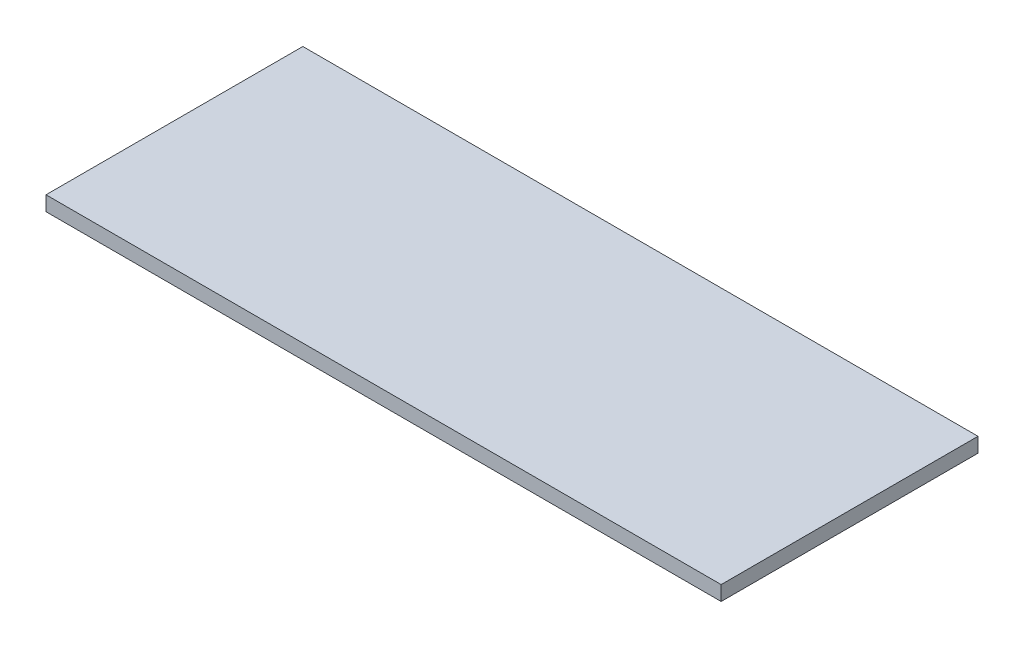
SolidWorks part; units mm, degrees
ref_plane "Front Plane" through (0, 0, 0) normal (0, 0, 1) x (1, 0, 0)
ref_plane "Top Plane" through (0, 0, 0) normal (0, 1, 0) x (1, 0, 0)
ref_plane "Right Plane" through (0, 0, 0) normal (1, 0, 0) x (0, 0, -1)
sketch "Sketch1" plane through (0, 0, 0) normal (0, 1, 0) x (1, 0, 0)
  line L1 (0, 0) -> (460, 0)
  line L2 (0, 0) -> (0, 175)
  line L3 (0, 175) -> (460, 175)
  line L4 (460, 0) -> (460, 175)
  dimension "D1" = 460
  dimension "D2" = 175
extrude "Boss-Extrude1" add sketch "Sketch1" along normal blind 10
